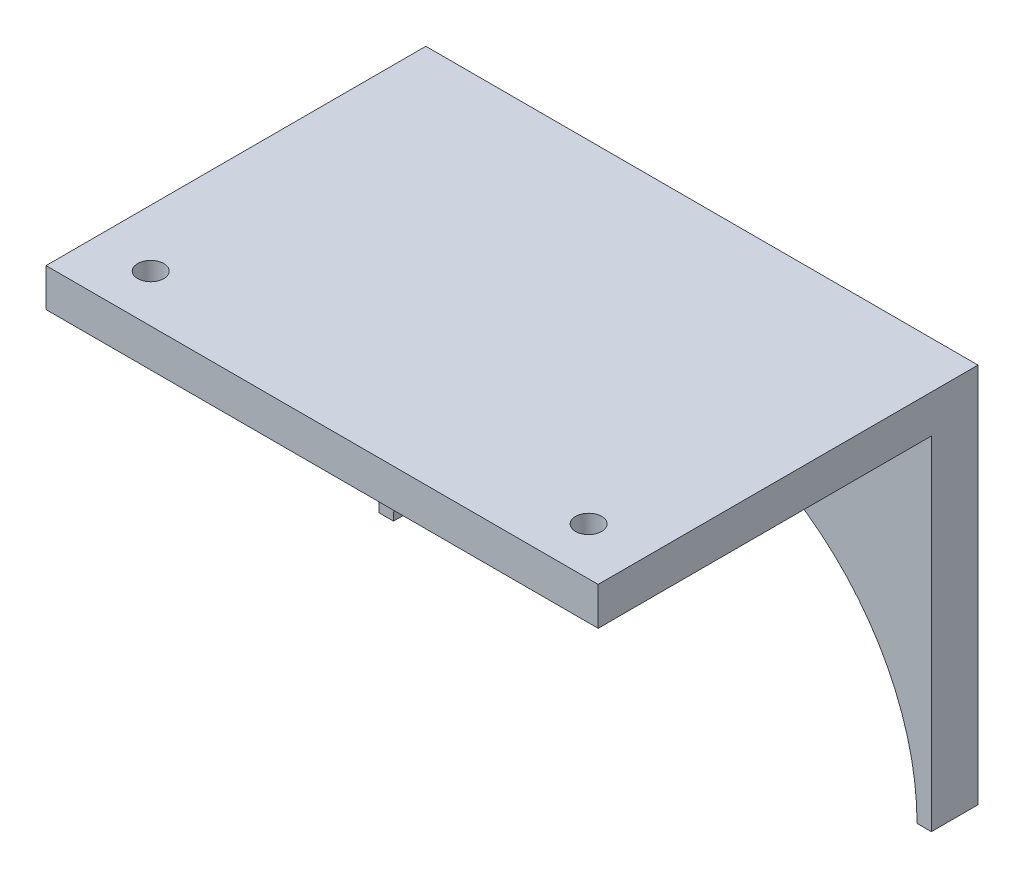
SolidWorks part; units mm, degrees
ref_plane "Front Plane" through (0, 0, 0) normal (0, 0, 1) x (1, 0, 0)
ref_plane "Top Plane" through (0, 0, 0) normal (0, 1, 0) x (1, 0, 0)
ref_plane "Right Plane" through (0, 0, 0) normal (1, 0, 0) x (0, 0, -1)
sketch "Sketch1" plane through (0, 0, 0) normal (0, 0, 1) x (1, 0, 0)
  line L0 (50, 0) -> (58, 0)
  line L1 (58, 0) -> (58, 80)
  line L2 (-50, 0) -> (-58, 0)
  line L3 (-58, 0) -> (-58, 80)
  line L4 (-58, 80) -> (58, 80)
  arc A0 (50, 0) -> (-50, 0) centre (0, 0) ccw
  dimension "D1" = 100
  dimension "D5" = 8
  dimension "D7" = 80
extrude "Boss-Extrude1" add sketch "Sketch1" along normal blind 1.8
sketch "Sketch4" plane through (0, 0, 1.8) normal (0, 0, 1) x (1, 0, 0)
  line L0 (-55, 0) -> (-58, 0)
  line L1 (-58, 0) -> (-58, 80)
  line L2 (-58, 80) -> (58, 80)
  line L3 (58, 80) -> (58, 0)
  line L4 (55, 0) -> (58, 0)
  line L5 (58, 80) -> (-58, 80) construction
  arc A0 (50, 0) -> (-50, 0) centre (0, 0) ccw construction
  arc A3 (50, 0) -> (-50, 0) centre (0, 0) ccw
  arc A4 (50, 0) -> (-50, 0) centre (0, 0) ccw
  arc A6 (55, 0) -> (-55, 0) centre (0, 0) ccw
  arc A7 (55, 0) -> (-55, 0) centre (0, 0) ccw
  dimension "D1" = 5
extrude "Boss-Extrude4" add sketch "Sketch4" along normal blind 8
sketch "Sketch5" plane through (0, 80, 0) normal (0, 1, 0) x (1, 0, 0)
  line L0 (-58, -79.8) -> (58, -79.8)
  line L1 (58, -9.8) -> (-58, -9.8)
  line L2 (-58, -9.8) -> (-58, -79.8)
  line L3 (58, -79.8) -> (58, -9.8)
  dimension "D1" = 70
extrude "Boss-Extrude5" add sketch "Sketch5" against normal blind 8
sketch "Sketch6" plane through (0, 72, 0) normal (0, -1, 0) x (1, 0, 0)
  line L0 (-58, 79.8) -> (58, 79.8) construction
  line L1 (-58, 9.8) -> (-58, 79.8) construction
  line L2 (58, 79.8) -> (58, 9.8) construction
  circle A0 centre (-46, 69.8) radius 2.75
  circle A1 centre (46, 69.8) radius 2.75
  dimension "D2" = 5.5
  dimension "D1" = 10
  dimension "D3" = 12
  dimension "D4" = 12
extrude "Cut-Extrude1" cut sketch "Sketch6" against normal through all
